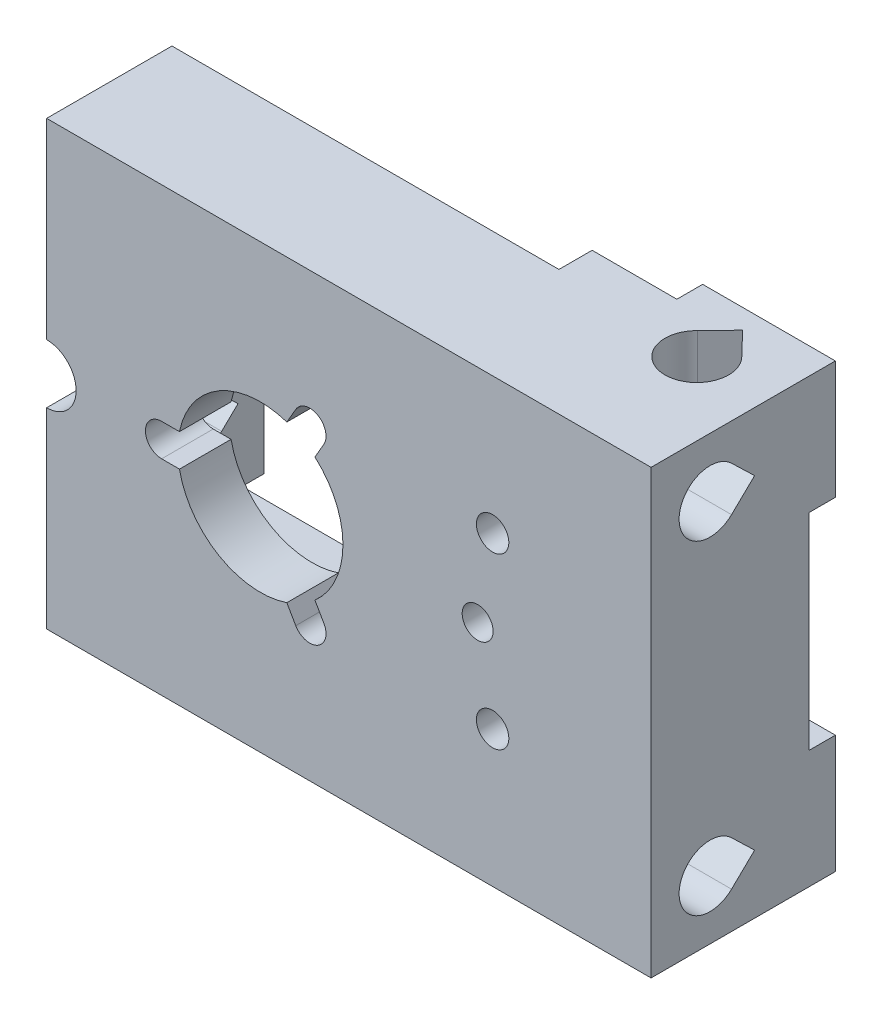
SolidWorks part; units mm, degrees
ref_plane "Front Plane" through (0, 0, 0) normal (0, 0, 1) x (1, 0, 0)
ref_plane "Top Plane" through (0, 0, 0) normal (0, 1, 0) x (1, 0, 0)
ref_plane "Right Plane" through (0, 0, 0) normal (1, 0, 0) x (0, 0, -1)
ref_plane "Plane1" through (-39, 0, 0) normal (-1, 0, 0) x (0, -1, 0)
sketch "Sketch1" plane through (-39, 0, 0) normal (-1, 0, 0) x (0, -1, 0)
  line L0 (22, 15.7539) -> (18.9788, 18.8824)
  line L1 (25.0212, 18.8824) -> (22, 15.7539)
  line L2 (-18.9788, 18.8824) -> (-22, 15.7539)
  line L3 (-22, 15.7539) -> (-25.0212, 18.8824)
  line L4 (-30, 29.8) -> (-30, 4.8)
  line L5 (-30, 4.8) -> (30, 4.8)
  line L6 (30, 4.8) -> (30, 29.8)
  line L7 (30, 29.8) -> (-30, 29.8)
  arc A0 (18.9788, 18.8824) -> (25.0212, 18.8824) centre (22, 21.8) cw
  arc A1 (-25.0212, 18.8824) -> (-18.9788, 18.8824) centre (-22, 21.8) cw
extrude "Boss-Extrude1" add sketch "Sketch1" against normal blind 82
ref_plane "Plane2" through (36.0212, 0, 0) normal (-1, 0, 0) x (0, 0, 1)
ref_plane "Plane3" through (0, 0, 0) normal (0, -1, 0) x (1, 0, 0)
ref_plane "Plane4" through (33, 0, 0) normal (1, 0, 0) x (0, 0, -1)
ref_plane "Plane5" through (29.9788, 0, 0) normal (1, 0, 0) x (0, 0, -1)
ref_plane "Plane6" through (0, 0, 10.8824) normal (0, 0, -1) x (-1, 0, 0)
sketch "Sketch39" plane through (0, 0, 4.8) normal (0, 0, -1) x (-1, 0, 0)
  line L0 (-28, 14) -> (-28, -14)
  line L1 (-28, -14) -> (-25, -14)
  line L2 (-25, -14) -> (-25, -30)
  line L3 (-25, -30) -> (39, -30)
  line L4 (39, -30) -> (39, 30)
  line L5 (39, 30) -> (-25, 30)
  line L6 (-25, 30) -> (-25, 14)
  line L7 (-25, 14) -> (-28, 14)
extrude "Cut-Extrude7" cut sketch "Sketch39" against normal blind 3.5
ref_plane "Plane7" through (0, -30, 0) normal (0, -1, 0) x (1, 0, 0)
sketch "Sketch50" plane through (0, -30, 0) normal (0, -1, 0) x (1, 0, 0)
  line L0 (13.5, 8.3) -> (13.5, 12.8)
  line L1 (13.5, 12.8) -> (-39, 12.8)
  line L2 (-39, 12.8) -> (-39, 8.3)
  line L3 (-39, 8.3) -> (13.5, 8.3)
extrude "Cut-Extrude9" cut sketch "Sketch50" against normal through all
sketch "Sketch51" plane through (0, 0, 12.8) normal (0, 0, -1) x (-1, 0, 0)
  line L0 (29.5, -17) -> (29.5, 17)
  line L1 (29.5, 17) -> (39, 17)
  line L2 (39, 17) -> (39, -17)
  line L3 (39, -17) -> (29.5, -17)
extrude "Boss-Extrude2" add sketch "Sketch51" along normal blind 3
sketch "Sketch52" plane through (0, 0, 12.8) normal (0, 0, -1) x (-1, 0, 0)
  line L0 (-13.5, -17) -> (29.5, -17)
  line L1 (29.5, -17) -> (29.5, 17)
  line L2 (29.5, 17) -> (-13.5, 17)
  line L3 (-13.5, 17) -> (-13.5, -17)
extrude "Cut-Extrude10" cut sketch "Sketch52" against normal blind 10
ref_plane "Plane8" through (-29.5, 0, 0) normal (1, 0, 0) x (0, 0, -1)
sketch "Sketch63" plane through (-29.5, 0, 0) normal (1, 0, 0) x (0, 0, -1)
  line L0 (-22.8, 4.8927) -> (-19.15, 2.7853)
  line L1 (-19.15, 2.7853) -> (-15.559, 4.8586)
  line L2 (-15.559, 4.8586) -> (-13.3415, 7)
  line L3 (-13.3415, 7) -> (-15.559, 9.1414)
  line L4 (-15.559, 9.1414) -> (-19.15, 11.2147)
  line L5 (-19.15, 11.2147) -> (-22.8, 9.1073)
  line L6 (-22.8, 9.1073) -> (-22.8, 4.8927)
extrude "Cut-Extrude11" cut sketch "Sketch63" against normal blind 4
sketch "Sketch75" plane through (-29.5, 0, 0) normal (1, 0, 0) x (0, 0, -1)
  line L0 (-15.559, -4.8586) -> (-19.15, -2.7853)
  line L1 (-19.15, -2.7853) -> (-22.8, -4.8927)
  line L2 (-22.8, -4.8927) -> (-22.8, -9.1073)
  line L3 (-22.8, -9.1073) -> (-19.15, -11.2147)
  line L4 (-19.15, -11.2147) -> (-15.559, -9.1414)
  line L5 (-15.559, -9.1414) -> (-13.3415, -7)
  line L6 (-13.3415, -7) -> (-15.559, -4.8586)
extrude "Cut-Extrude12" cut sketch "Sketch75" against normal blind 4
sketch "Sketch76" plane through (0, 0, 4.8) normal (0, 0, -1) x (-1, 0, 0)
  line L0 (-25, -18.6937) -> (-25, -14)
  line L1 (-25, -14) -> (-29.0993, -14)
  arc A0 (-29.0993, -14) -> (-25, -18.6937) centre (-21.5, -11.5) ccw
extrude "Cut-Extrude13" cut sketch "Sketch76" against normal blind 3.5
sketch "Sketch77" plane through (0, 0, 4.8) normal (0, 0, -1) x (-1, 0, 0)
  line L0 (-29.0993, 14) -> (-25, 14)
  line L1 (-25, 14) -> (-25, 18.6937)
  arc A0 (-25, 18.6937) -> (-29.0993, 14) centre (-21.5, 11.5) ccw
extrude "Cut-Extrude14" cut sketch "Sketch77" against normal blind 3.5
ref_plane "Plane9" through (-33.5, 0, 0) normal (1, 0, 0) x (0, 0, -1)
sketch "Sketch89" plane through (-33.5, 0, 0) normal (1, 0, 0) x (0, 0, -1)
  line L0 (-15.983, 7) -> (-17.6218, 8.5825)
  line L1 (-17.6218, 5.4175) -> (-15.983, 7)
  arc A0 (-17.6218, 8.5825) -> (-17.6218, 5.4175) centre (-19.15, 7) ccw
extrude "Cut-Extrude15" cut sketch "Sketch89" against normal through all
sketch "Sketch90" plane through (0, 0, 29.8) normal (0, 0, 1) x (1, 0, 0)
  line L0 (-23.4, -2.2) -> (-20.9818, -2.2)
  line L1 (-6.4144, -10.6105) -> (-5.2053, -12.7047)
  line L2 (-1.3947, -10.5047) -> (-2.6038, -8.4105)
  line L3 (-2.6038, 8.4105) -> (-1.3947, 10.5047)
  line L4 (-5.2053, 12.7047) -> (-6.4144, 10.6105)
  line L5 (-20.9818, 2.2) -> (-23.4, 2.2)
  arc A0 (-23.4, 2.2) -> (-23.4, -2.2) centre (-23.4, 0) ccw
  arc A1 (-20.9818, -2.2) -> (-6.4144, -10.6105) centre (-10, 0) ccw
  arc A2 (-5.2053, -12.7047) -> (-1.3947, -10.5047) centre (-3.3, -11.6047) ccw
  arc A3 (-2.6038, -8.4105) -> (-2.6038, 8.4105) centre (-10, 0) ccw
  arc A4 (-1.3947, 10.5047) -> (-5.2053, 12.7047) centre (-3.3, 11.6047) ccw
  arc A5 (-6.4144, 10.6105) -> (-20.9818, 2.2) centre (-10, 0) ccw
extrude "Cut-Extrude16" cut sketch "Sketch90" against normal through all
sketch "Sketch103" plane through (-33.5, 0, 0) normal (1, 0, 0) x (0, 0, -1)
  line L0 (-17.6218, -8.5825) -> (-15.983, -7)
  line L1 (-15.983, -7) -> (-17.6218, -5.4175)
  arc A0 (-17.6218, -5.4175) -> (-17.6218, -8.5825) centre (-19.15, -7) ccw
extrude "Cut-Extrude17" cut sketch "Sketch103" against normal through all
ref_plane "Plane10" through (0, 0, 8.3) normal (0, 0, -1) x (-1, 0, 0)
sketch "Sketch116" plane through (0, 0, 8.3) normal (0, 0, -1) x (-1, 0, 0)
  line L0 (-19.5, 4.2147) -> (-23.091, 2.1414)
  line L1 (-23.091, 2.1414) -> (-23.091, -2.1414)
  line L2 (-23.091, -2.1414) -> (-19.5, -4.2147)
  line L3 (-19.5, -4.2147) -> (-15.85, -2.1073)
  line L4 (-15.85, -2.1073) -> (-15.85, 2.1073)
  line L5 (-15.85, 2.1073) -> (-19.5, 4.2147)
extrude "Cut-Extrude18" cut sketch "Sketch116" against normal blind 15
hole_wizard "Hole1" positions "Sketch118" profile "Sketch117" legacy
sketch "Sketch118" plane through (0, 0, 23.3) normal (0, 0, -1) x (-1, 0, 0)
  point P0 (-19.4705, 0.017)
sketch "Sketch117" plane through (19.4705, 0.017, 23.3) normal (1, 0, 0) x (0, 1, 0)
  line L0 (0, 0) -> (0, 6.5)
  line L1 (0, 6.5) -> (2.1, 6.5)
  line L2 (2.1, 6.5) -> (2.1, 0)
  line L3 (2.1, 0) -> (0, 0)
  line L4 (0, 110) -> (0, -10) construction
  dimension "Diameter" = 4.2
  dimension "Depth" = 6.5
hole_wizard "Hole2" positions "Sketch120" profile "Sketch119" legacy
sketch "Sketch120" plane through (0, 0, 8.3) normal (0, 0, -1) x (-1, 0, 0)
  point P0 (-21.5, 11.5)
sketch "Sketch119" plane through (21.5, 11.5, 8.3) normal (1, 0, 0) x (0, 1, 0)
  line L0 (0, 0) -> (0, 21.5)
  line L1 (0, 21.5) -> (2.2, 21.5)
  line L2 (2.2, 21.5) -> (2.2, 0)
  line L3 (2.2, 0) -> (0, 0)
  line L4 (0, 110) -> (0, -10) construction
  dimension "Diameter" = 4.4
  dimension "Depth" = 21.5
hole_wizard "Hole3" positions "Sketch122" profile "Sketch121" legacy
sketch "Sketch122" plane through (0, 0, 8.3) normal (0, 0, -1) x (-1, 0, 0)
  point P0 (-21.5, -11.5)
sketch "Sketch121" plane through (21.5, -11.5, 8.3) normal (1, 0, 0) x (0, 1, 0)
  line L0 (0, 0) -> (0, 21.5)
  line L1 (0, 21.5) -> (2.2, 21.5)
  line L2 (2.2, 21.5) -> (2.2, 0)
  line L3 (2.2, 0) -> (0, 0)
  line L4 (0, 110) -> (0, -10) construction
  dimension "Diameter" = 4.4
  dimension "Depth" = 21.5
hole_wizard "Hole4" positions "Sketch124" profile "Sketch123" legacy
sketch "Sketch124" plane through (0, 0, 9.8) normal (0, 0, -1) x (-1, 0, 0)
  point P0 (39, 0)
sketch "Sketch123" plane through (-39, 0, 9.8) normal (1, 0, 0) x (0, 1, 0)
  line L0 (0, 0) -> (0, 20)
  line L1 (0, 20) -> (4, 20)
  line L2 (4, 20) -> (4, 0)
  line L3 (4, 0) -> (0, 0)
  line L4 (0, 110) -> (0, -10) construction
  dimension "Diameter" = 8
  dimension "Depth" = 20
sketch "Sketch125" plane through (0, 0, 4.8) normal (0, 0, -1) x (-1, 0, 0)
  line L0 (-43, 30) -> (-43, -30) construction
  line L1 (-43, -13.97) -> (-37.92, -13.97)
  line L2 (-43, -13.97) -> (-43, 13.97)
  line L3 (-43, 13.97) -> (-37.92, 13.97)
  line L4 (-37.92, -13.97) -> (-37.92, 13.97)
  line L5 (-28, 0) -> (-37.92, 0) construction
  line L6 (-28, 14) -> (-28, -14) construction
  dimension "D1" = 27.94
  dimension "D2" = 5.08
extrude "Cut-Extrude19" cut sketch "Sketch125" against normal blind 3.556
sketch "Sketch126" plane through (0, 0, 4.8) normal (0, 0, -1) x (-1, 0, 0)
  line L1 (-28, -14) -> (-37.92, -14)
  line L2 (-28, -14) -> (-28, 14.0177)
  line L3 (-28, 14.0177) -> (-37.92, 14.0177)
  line L4 (-37.92, -14) -> (-37.92, 14.0177)
  line L5 (-37.92, -13.97) -> (-37.92, 13.97) construction
extrude "Cut-Extrude20" cut sketch "Sketch126" against normal blind 20.066
sketch "Sketch128" plane through (0, 30, 0) normal (0, 1, 0) x (1, 0, 0)
  line L0 (30.0945, -10.5839) -> (33.094, -7.4778)
  line L1 (33.094, -7.4778) -> (36.0935, -10.5839)
  line L3 (33.094, -13.69) -> (33.094, -7.4778) construction
  line L5 (37.92, -4.8) -> (29.0993, -4.8) construction
  line L6 (43, -4.8) -> (25, -4.8) construction
  line L9 (43, -29.8) -> (43, -4.8) construction
  arc A0 (30.0945, -10.5839) -> (36.0935, -10.5839) centre (33.094, -13.69) ccw
  point P3 (33.5097, -4.8)
  point P11 (43, -12.6781)
  dimension "D1" = 4.318
  dimension "D2" = 4.318
  dimension "D3" = 88
  dimension "D4" = 8.89
  dimension "D5" = 9.906
extrude "Cut-Extrude21" cut sketch "Sketch128" against normal through all
